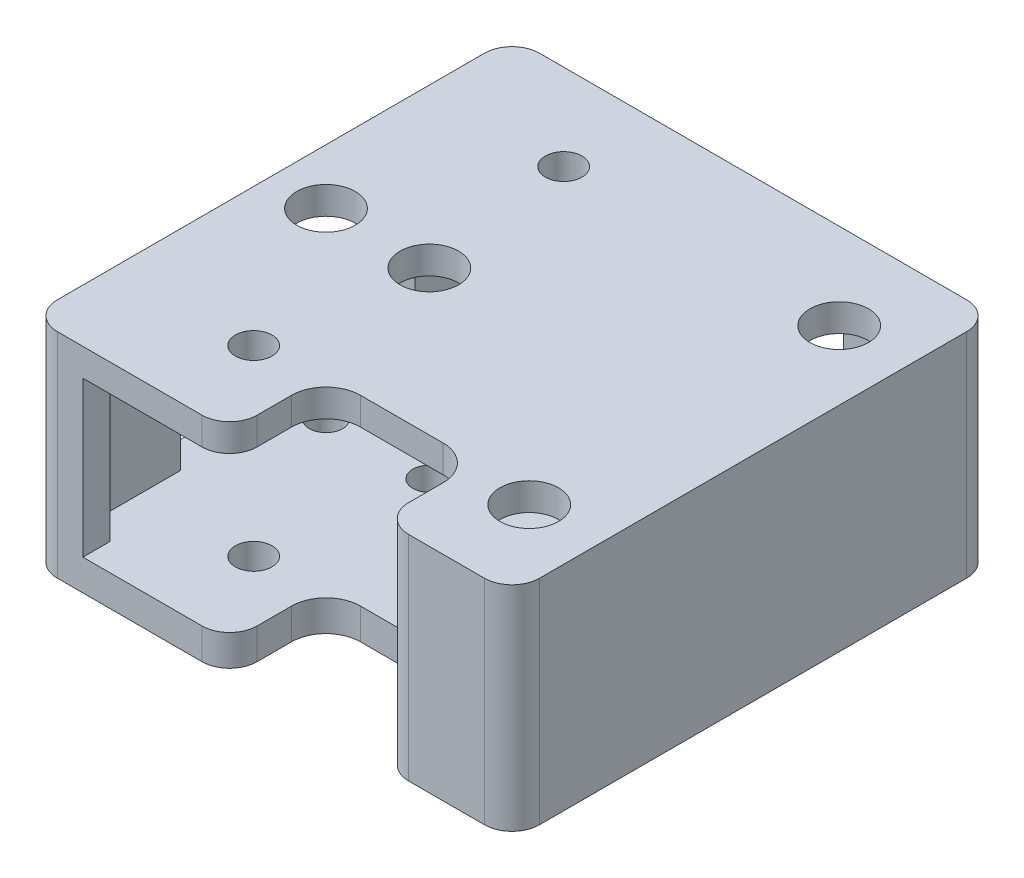
SolidWorks part; units mm, degrees
ref_plane "Front Plane" through (0, 0, 0) normal (0, 0, 1) x (1, 0, 0)
ref_plane "Top Plane" through (0, 0, 0) normal (0, 1, 0) x (1, 0, 0)
ref_plane "Right Plane" through (0, 0, 0) normal (1, 0, 0) x (0, 0, -1)
sketch "Sketch1" plane through (0, 0, 0) normal (0, 1, 0) x (1, 0, 0)
  line L0 (-55, 0) -> (55, 0) construction
  line L1 (-31, -35) -> (31, -35)
  line L2 (-35, -31) -> (-35, 31)
  line L3 (-31, 35) -> (31, 35)
  line L4 (35, -31) -> (35, 31)
  line L5 (-35, -35) -> (35, 35) construction
  line L6 (-35, 35) -> (35, -35) construction
  line L8 (-15, 22.5) -> (25, 22.5) construction
  line L9 (-15, 22.5) -> (-15, -22.5) construction
  line L10 (-15, -22.5) -> (25, -22.5) construction
  line L11 (25, 22.5) -> (25, -22.5) construction
  circle A0 centre (25, 22.5) radius 2.6605
  circle A1 centre (25, -22.5) radius 2.6605
  circle A2 centre (-15, -22.5) radius 2.6605
  circle A3 centre (-15, 22.5) radius 2.6605
  circle A4 centre (-12, 0) radius 2.4121
  circle A5 centre (-27, 0) radius 2.4122
  arc A6 (-31, -35) -> (-35, -31) centre (-31, -31) cw
  arc A7 (31, -35) -> (35, -31) centre (31, -31) ccw
  arc A8 (31, 35) -> (35, 31) centre (31, 31) cw
  arc A9 (-35, 31) -> (-31, 35) centre (-31, 31) cw
  point P0 (0, 0)
  point P22 (25, 0)
  dimension "D6" = 4.8243
  dimension "D7" = 5.321
  dimension "D8" = 4
  dimension "D1" = 70
  dimension "D2" = 40
  dimension "D3" = 45
  dimension "D4" = 15
  dimension "D5" = 8
  dimension "D9" = 10
extrude "Boss-Extrude1" add sketch "Sketch1" along normal blind 4.5
sketch "Sketch2" plane through (0, 4.5, 0) normal (0, 1, 0) x (1, 0, 0)
  line L0 (-27.2898, 35) -> (-31, 35)
  line L1 (31, 35) -> (-31, 35) construction
  line L2 (-31.1, 31) -> (-31.1, 17)
  line L3 (-35, 31) -> (-35, -31) construction
  line L5 (-31, -35) -> (-27.2898, -35)
  line L6 (-31, -35) -> (31, -35) construction
  line L7 (17, -35) -> (31, -35)
  line L8 (35, -31) -> (35, 31)
  line L9 (31, 35) -> (17, 35)
  line L10 (17, 35) -> (17, 31.1)
  line L11 (-31.1, 17) -> (-35, 17)
  line L12 (17, 31.1) -> (31, 31.1)
  line L13 (31.1, 31) -> (31.1, -31)
  line L14 (31, -31.1) -> (17, -31.1)
  line L15 (17, -31.1) -> (17, -35)
  line L16 (-27.2898, -35) -> (-27.2898, -31.1)
  line L17 (-27.2898, -31.1) -> (-31, -31.1)
  line L19 (-31, 31.1) -> (-27.2898, 31.1)
  line L20 (-27.2898, 31.1) -> (-27.2898, 35)
  line L21 (-35, 17) -> (-35, 31)
  line L22 (-31.1, -31) -> (-31.1, -17)
  line L23 (-31.1, -17) -> (-35, -17)
  line L24 (-35, -17) -> (-35, -31)
  arc A0 (-31, 35) -> (-35, 31) centre (-31, 31) ccw
  arc A1 (-35, -31) -> (-31, -35) centre (-31, -31) ccw
  arc A2 (31, -35) -> (35, -31) centre (31, -31) ccw
  arc A3 (31, -35) -> (35, -31) centre (31, -31) ccw construction
  arc A4 (35, 31) -> (31, 35) centre (31, 31) ccw
  arc A5 (31, 31.1) -> (31.1, 31) centre (31, 31) cw
  arc A6 (31.1, -31) -> (31, -31.1) centre (31, -31) cw
  arc A7 (-31, -31.1) -> (-31.1, -31) centre (-31, -31) cw
  arc A8 (-31.1, 31) -> (-31, 31.1) centre (-31, 31) cw
  circle A9 centre (-15, -22.5) radius 15 construction
  dimension "D1" = 30
  dimension "D2" = 18
  dimension "D3" = 3.9
  dimension "D4" = 18
extrude "Boss-Extrude2" add sketch "Sketch2" along normal blind 22.5
sketch "Sketch3" plane through (0, 27, 0) normal (0, 1, 0) x (1, 0, 0)
  line L0 (-31, 35) -> (31, 35)
  line L1 (35, 31) -> (35, -31)
  line L2 (31, -35) -> (-31, -35)
  line L3 (-35, -31) -> (-35, 31)
  arc A0 (31, 35) -> (35, 31) centre (31, 31) cw
  arc A1 (35, -31) -> (31, -35) centre (31, -31) cw
  arc A2 (-31, -35) -> (-35, -31) centre (-31, -31) cw
  arc A3 (-35, 31) -> (-31, 35) centre (-31, 31) cw
  circle A4 centre (-15, 22.5) radius 2.6605
  circle A5 centre (25, 22.5) radius 4.25
  circle A6 centre (25, -22.5) radius 4.25
  circle A7 centre (-15, -22.5) radius 2.6605
  circle A8 centre (-12, 0) radius 4.25
  circle A9 centre (-27, 0) radius 4.25
  circle A10 centre (-15, 22.5) radius 2.6605 construction
  circle A11 centre (-15, -22.5) radius 2.6605 construction
  dimension "D1" = 8.5
extrude "Boss-Extrude3" add sketch "Sketch3" along normal blind 4
sketch "Sketch4" plane through (0, 0, 0) normal (0, 1, 0) x (1, 0, 0)
  line L0 (-31, -35) -> (31, -35) construction
  line L1 (-1, -21) -> (11, -21)
  line L2 (-6, -26) -> (-6, -35)
  line L3 (-6, -35) -> (16, -35)
  line L4 (16, -26) -> (16, -35)
  line L11 (-15, -22.5) -> (25, -22.5) construction
  line L12 (5, -22.5) -> (5, -35) construction
  arc A0 (11, -21) -> (16, -26) centre (11, -26) cw
  arc A1 (-1, -21) -> (-6, -26) centre (-1, -26) ccw
  point P10 (5, -35)
  point P13 (16, -21)
  point P16 (-6, -21)
  dimension "D3" = 5
  dimension "D1" = 22
  dimension "D2" = 14
extrude "Cut-Extrude2" cut sketch "Sketch4" along normal through all
fillet "Fillet1" radius 4 3 edges at (16, 2.25, 35) (-6, 2.25, 35) (-6, 29, 35)
ref_plane "Plane1" through (5, 0, 0) normal (1, 0, 0) x (0, 0, -1)
